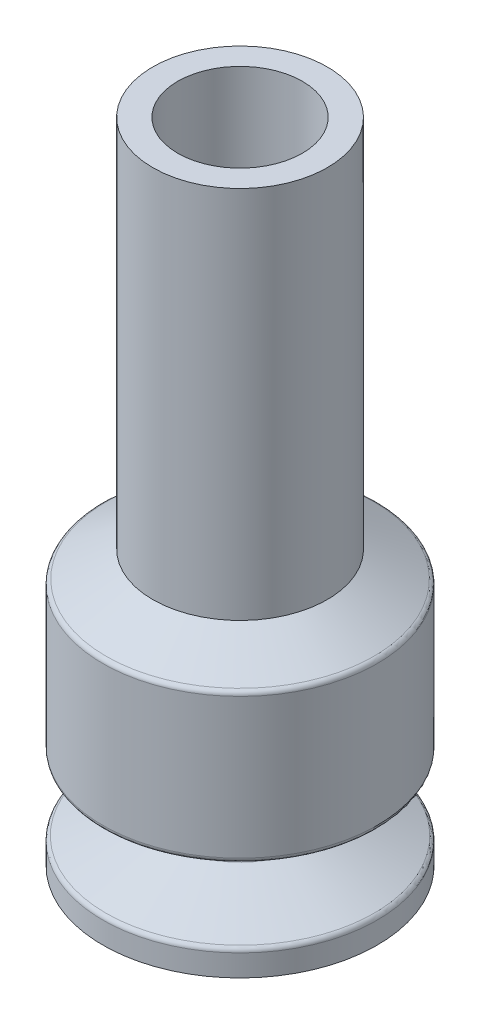
SolidWorks part; units mm, degrees
material "Silicon"
ref_plane "Front Plane" through (0, 0, 0) normal (0, 0, 1) x (1, 0, 0)
ref_plane "Top Plane" through (0, 0, 0) normal (0, 1, 0) x (1, 0, 0)
ref_plane "Right Plane" through (0, 0, 0) normal (1, 0, 0) x (0, 0, -1)
sketch "Sketch1" plane through (0, 0, 0) normal (0, 0, 1) x (1, 0, 0)
  line L0 (0, 0) -> (0, 11) construction
  line L1 (5.5, 10.6927) -> (5.5, 0) construction
  line L2 (2.5, 11) -> (2.5, 0) construction
  line L4 (5.5, 9.777) -> (5.5, 4.1599)
  line L5 (5.4, 3.9867) -> (2.8427, 2.5102)
  line L10 (2.8625, 2.1538) -> (5.3802, 1.0524)
  line L11 (5.5, 0.8692) -> (5.5, 0)
  line L13 (5, 9.4258) -> (5, 4.4486)
  line L14 (4.9, 4.2754) -> (1.9073, 2.5475)
  line L15 (1.9371, 2.0129) -> (4.8802, 0.7254)
  line L16 (5, 0.5422) -> (5, 0)
  line L17 (2.5, 11) -> (2.5, 10.4684)
  line L18 (5.5, 0) -> (5, 0)
  line L19 (2.3303, 10.5297) -> (5, 9.5663) construction
  line L20 (1.3933, 2.2507) -> (5, 0.673) construction
  line L21 (5, 4.3331) -> (1.3933, 2.2507) construction
  line L22 (5.5, 4.0445) -> (2.5, 2.3124) construction
  line L23 (2.5, 2.3124) -> (5.5, 1) construction
  line L24 (5, 9.5663) -> (5, 4.3331) construction
  line L25 (5.5, 9.9174) -> (5.5, 4.0445) construction
  line L26 (5.5, 1) -> (5.5, 0) construction
  line L27 (5, 0.673) -> (5, 0) construction
  line L28 (2.5, 11) -> (5.5, 9.9174) construction
  line L31 (3.5, 11) -> (2.5, 11)
  line L32 (5.3679, 9.9651) -> (3.5, 11)
  line L33 (4.8679, 9.614) -> (3.5, 10.4684)
  line L34 (3.5, 10.4684) -> (2.5, 10.4684)
  arc A0 (1.9371, 2.0129) -> (1.9073, 2.5475) centre (2.0573, 2.2877) cw
  arc A1 (2.8427, 2.5102) -> (2.8625, 2.1538) centre (2.9427, 2.337) ccw
  arc A2 (5, 4.4486) -> (4.9, 4.2754) centre (4.8, 4.4486) cw
  arc A3 (5.5, 4.1599) -> (5.4, 3.9867) centre (5.3, 4.1599) cw
  arc A4 (5.5, 0.8692) -> (5.3802, 1.0524) centre (5.3, 0.8692) ccw
  arc A5 (5, 0.5422) -> (4.8802, 0.7254) centre (4.8, 0.5422) ccw
  arc A6 (5, 9.4258) -> (4.8679, 9.614) centre (4.8, 9.4258) ccw
  arc A7 (5.5, 9.777) -> (5.3679, 9.9651) centre (5.3, 9.777) ccw
  point P24 (2.5, 2.3124)
  dimension "D7" = 0.3
  dimension "D8" = 0.2
  dimension "D9" = 0.2
  dimension "D10" = 0.2
  dimension "D11" = 0.2
  dimension "D6" = 0.2
  dimension "D12" = 0.2
  dimension "D13" = 0.2
  dimension "D1" = 11
  dimension "D2" = 5.5
  dimension "D3" = 11
  dimension "D4" = 0.5
  dimension "D5" = 2.5
  dimension "D14" = 1
  dimension "D15" = 1
revolve "Revolve5" add sketch "Sketch1" angle 360 about L0
sketch "Sketch2" plane through (0, 11, 0) normal (0, 1, 0) x (1, 0, 0)
  circle A0 centre (0, 0) radius 3.5
  circle A1 centre (0, 0) radius 2.5
extrude "Boss-Extrude1" add sketch "Sketch2" along normal blind 15
